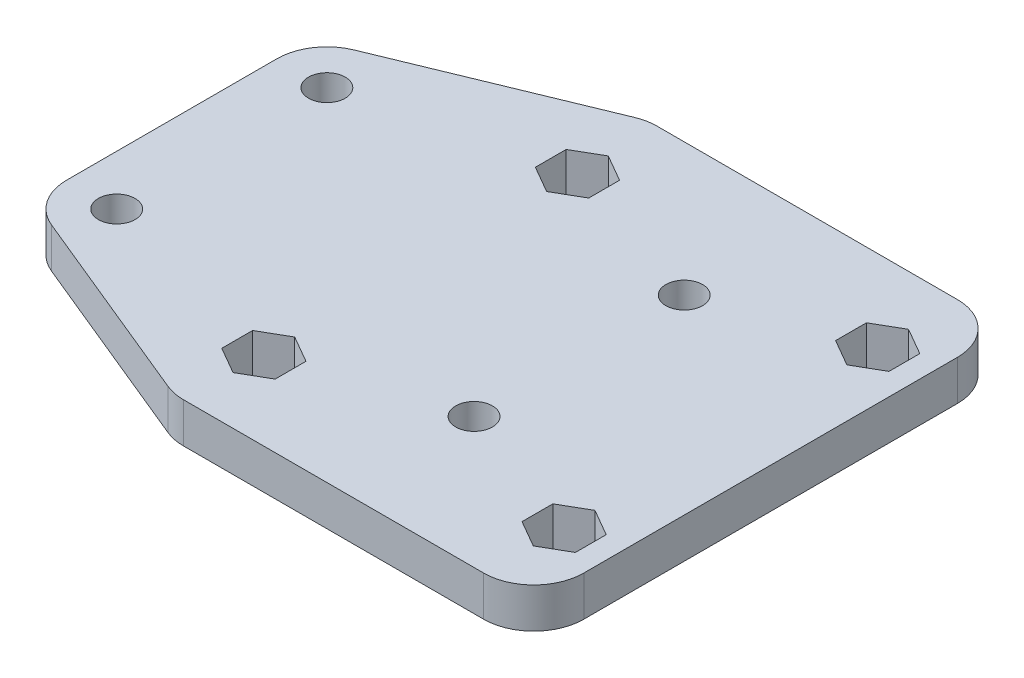
SolidWorks part; units mm, degrees
ref_plane "Front Plane" through (0, 0, 0) normal (0, 0, 1) x (1, 0, 0)
ref_plane "Top Plane" through (0, 0, 0) normal (0, 1, 0) x (1, 0, 0)
ref_plane "Right Plane" through (0, 0, 0) normal (1, 0, 0) x (0, 0, -1)
sketch "Sketch1" plane through (0, 0, 0) normal (0, 1, 0) x (1, 0, 0)
  line L0 (-24.7997, -23.6438) -> (-19.7997, -23.6438) construction
  line L7 (20.2003, -23.6438) -> (25.2003, -23.6438) construction
  line L10 (20.2003, 23.3562) -> (25.2003, 23.3562) construction
  line L13 (-24.7997, 23.3562) -> (-19.7997, 23.3562) construction
  line L16 (-59.75, 15.75) -> (-59.75, -15.75)
  line L17 (-55.1056, -22.6851) -> (-25.3556, -34.9351)
  line L18 (-22.5, -35.5) -> (22.5, -35.5)
  line L19 (30, -28) -> (30, 28)
  line L20 (22.5, 35.5) -> (-22.5, 35.5)
  line L21 (-25.3556, 34.9351) -> (-55.1056, 22.6851)
  circle A0 centre (-52.25, 15.75) radius 2.75
  circle A1 centre (-52.25, -15.75) radius 2.75
  circle A2 centre (1.4503, -15.8938) radius 2.75
  circle A3 centre (1.4503, 15.6062) radius 2.75
  circle A4 centre (-22.2997, -23.6438) radius 2.5
  circle A5 centre (22.7003, -23.6438) radius 2.5
  circle A6 centre (22.7003, 23.3562) radius 2.5
  circle A7 centre (-22.2997, 23.3562) radius 2.5
  circle A12 centre (-52.25, 15.75) radius 7.5
  circle A13 centre (-52.25, -15.75) radius 7.5
  circle A14 centre (-22.5, -28) radius 7.5
  circle A15 centre (22.5, -28) radius 7.5
  circle A16 centre (22.5, 28) radius 7.5
  circle A17 centre (-22.5, 28) radius 7.5
  dimension "D1" = 15
extrude "Boss-Extrude1" add sketch "Sketch1" along normal blind 6 contours A12 A0 | A17 L21 A12 L16 A13 L17 A14 L18 A15 L19 A16 L20 A3 A2 | A13 A1 | A14 A4 | A15 A5 | A16 A6 | A17 A7
sketch "Sketch2" plane through (0, 6, 0) normal (0, 1, 0) x (1, 0, 0)
  line L1 (-22.2997, 18.7374) -> (-18.2997, 21.0468)
  line L2 (-18.2997, 21.0468) -> (-18.2997, 25.6656)
  line L3 (-18.2997, 25.6656) -> (-22.2997, 27.975)
  line L4 (-22.2997, 27.975) -> (-26.2997, 25.6656)
  line L5 (-26.2997, 25.6656) -> (-26.2997, 21.0468)
  line L6 (-26.2997, 21.0468) -> (-22.2997, 18.7374)
  line L7 (-22.2997, -19.025) -> (-26.2997, -21.3344)
  line L8 (-26.2997, -21.3344) -> (-26.2997, -25.9532)
  line L9 (-26.2997, -25.9532) -> (-22.2997, -28.2626)
  line L10 (-22.2997, -28.2626) -> (-18.2997, -25.9532)
  line L11 (-18.2997, -25.9532) -> (-18.2997, -21.3344)
  line L12 (-18.2997, -21.3344) -> (-22.2997, -19.025)
  line L13 (18.7003, -25.9532) -> (22.7003, -28.2626)
  line L14 (22.7003, -28.2626) -> (26.7003, -25.9532)
  line L15 (26.7003, -25.9532) -> (26.7003, -21.3344)
  line L16 (26.7003, -21.3344) -> (22.7003, -19.025)
  line L17 (22.7003, -19.025) -> (18.7003, -21.3344)
  line L18 (18.7003, -21.3344) -> (18.7003, -25.9532)
  line L19 (22.7003, 18.7374) -> (26.7003, 21.0468)
  line L20 (26.7003, 21.0468) -> (26.7003, 25.6656)
  line L21 (26.7003, 25.6656) -> (22.7003, 27.975)
  line L22 (22.7003, 27.975) -> (18.7003, 25.6656)
  line L23 (18.7003, 25.6656) -> (18.7003, 21.0468)
  line L24 (18.7003, 21.0468) -> (22.7003, 18.7374)
  circle A0 centre (-22.2997, 23.3562) radius 4 construction
  circle A1 centre (-22.2997, -23.6438) radius 4 construction
  circle A2 centre (22.7003, -23.6438) radius 4 construction
  circle A3 centre (22.7003, 23.3562) radius 4 construction
  dimension "D1" = 8
extrude "Cut-Extrude1" cut sketch "Sketch2" against normal through all and the other way through all
